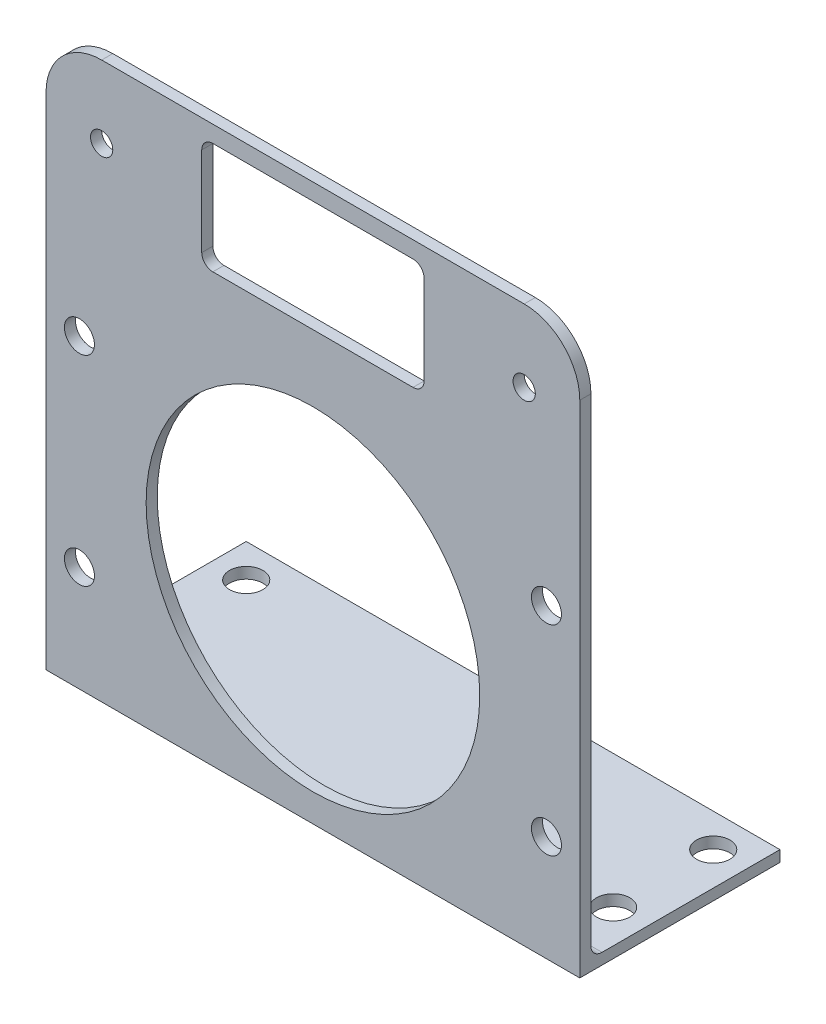
SolidWorks part; units mm, degrees
ref_plane "Front Plane" through (0, 0, 0) normal (0, 0, 1) x (1, 0, 0)
ref_plane "Top Plane" through (0, 0, 0) normal (0, 1, 0) x (1, 0, 0)
ref_plane "Right Plane" through (0, 0, 0) normal (1, 0, 0) x (0, 0, -1)
sketch "Sketch1" plane through (0, 0, 0) normal (0, 0, 1) x (1, 0, 0)
  line L1 (-24, 17.5) -> (24, 17.5)
  line L2 (-24, 17.5) -> (-24, -17.5)
  line L3 (-24, -17.5) -> (24, -17.5)
  line L4 (24, 17.5) -> (24, -17.5)
  line L5 (-24, 17.5) -> (24, -17.5) construction
  line L6 (-24, -17.5) -> (24, 17.5) construction
  point P0 (0, 0)
  dimension "D1" = 35
  dimension "D2" = 48
extrude "Boss-Extrude1" add sketch "Sketch1" along normal blind 1
sketch "Sketch2" plane through (0, 0, 0) normal (0, 0, -1) x (-1, 0, 0)
  line L0 (24, 17.5) -> (24, -17.5) construction
  line L1 (-24, -17.5) -> (24, -17.5)
  line L2 (-24, -17.5) -> (-24, -16.5)
  line L3 (-24, -16.5) -> (24, -16.5)
  line L4 (24, -17.5) -> (24, -16.5)
  dimension "D1" = 1
extrude "Boss-Extrude2" add sketch "Sketch2" along normal blind 17
fillet "Fillet1" radius 1 1 edges at (0, -16.5, 0)
sketch "Sketch3" plane through (0, 0, 1) normal (0, 0, 1) x (1, 0, 0)
  line L0 (-24, 17.5) -> (-24, -17.5) construction
  line L1 (24, 17.5) -> (-24, 17.5) construction
  line L4 (0, -55) -> (0, 55) construction
  circle A0 centre (-21, 10) radius 1.35
  circle A4 centre (0, 0) radius 15
  circle A5 centre (-21, -8) radius 1.35
  circle A6 centre (21, -8) radius 1.35
  circle A7 centre (21, 10) radius 1.35
  point P8 (-21, -8.5)
  point P9 (0, 0)
  dimension "D1" = 2.7
  dimension "D4" = 30
  dimension "D2" = 3
  dimension "D3" = 7.5
  dimension "D5" = 18
extrude "Cut-Extrude1" cut sketch "Sketch3" against normal through all
sketch "Sketch4" plane through (0, 17.5, 0) normal (0, 1, 0) x (1, 0, 0)
  line L1 (24, -1) -> (-24, -1)
  line L2 (24, -1) -> (24, 0)
  line L3 (24, 0) -> (-24, 0)
  line L4 (-24, -1) -> (-24, 0)
extrude "Boss-Extrude3" add sketch "Sketch4" along normal blind 15
sketch "Sketch5" plane through (0, 0, 1) normal (0, 0, 1) x (1, 0, 0)
  line L0 (0, -9.9) -> (0, 9.9) construction
  line L1 (-24, 32.5) -> (24, 32.5) construction
  line L3 (-10, 31) -> (10, 31)
  line L4 (-10, 31) -> (-10, 21)
  line L5 (-10, 21) -> (10, 21)
  line L6 (10, 31) -> (10, 21)
  line L7 (-10, 31) -> (10, 21) construction
  line L8 (-10, 21) -> (10, 31) construction
  circle A0 centre (-19, 26) radius 1
  circle A1 centre (19, 26) radius 1
  point P4 (0, 0)
  point P10 (0, 26)
  dimension "D1" = 2
  dimension "D2" = 2
  dimension "D3" = 38
  dimension "D4" = 19
  dimension "D5" = 6.5
  dimension "D6" = 20
  dimension "D7" = 10
extrude "Cut-Extrude2" cut sketch "Sketch5" against normal through all
fillet "Fillet2" radius 1 4 edges at (10, 21, 0.5) (10, 31, 0.5) (-10, 21, 0.5) (-10, 31, 0.5)
sketch "Sketch6" plane through (0, -16.5, 0) normal (0, 1, 0) x (1, 0, 0)
  line L0 (24, 17) -> (24, 1) construction
  line L1 (-24, 17) -> (24, 17) construction
  line L2 (-24, -1) -> (24, -1) construction
  line L3 (0, -9.9) -> (0, 9.9) construction
  circle A0 centre (21, 5) radius 1.5
  circle A1 centre (21, 14) radius 1.5
  circle A2 centre (-21, 5) radius 1.5
  circle A3 centre (-21, 14) radius 1.5
  point P10 (21, 5)
  dimension "D3" = 3
  dimension "D1" = 3
  dimension "D2" = 3
  dimension "D4" = 3
  dimension "D5" = 6
extrude "Cut-Extrude3" cut sketch "Sketch6" against normal through all
fillet "Fillet3" radius 5 2 edges at (-24, 32.5, 0.5) (24, 32.5, 0.5)
